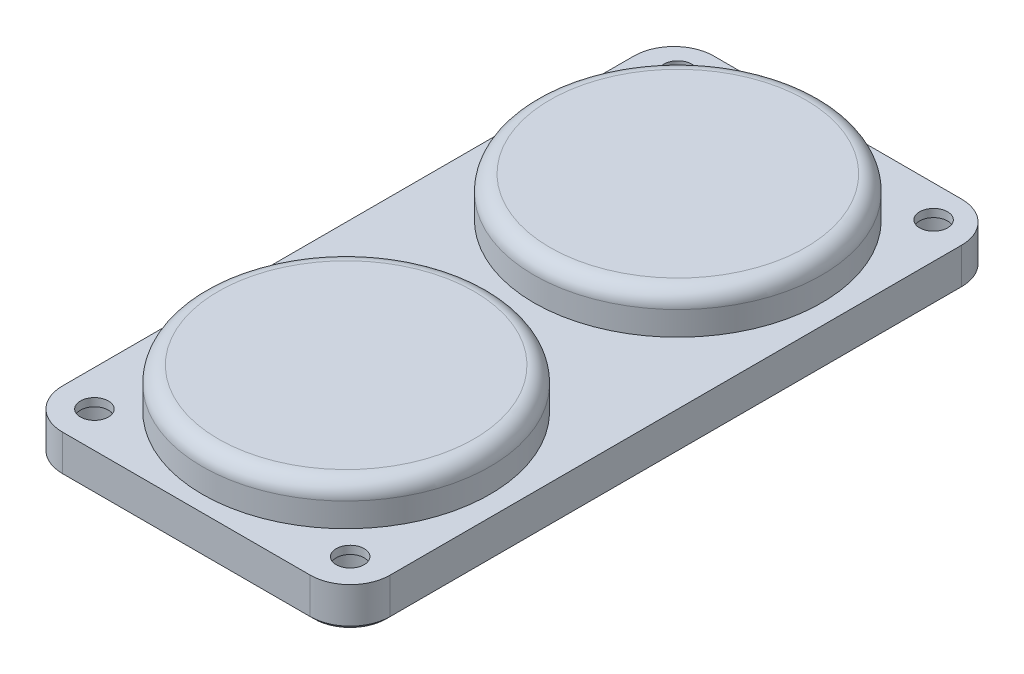
SolidWorks part; units mm, degrees
ref_plane "Front Plane" through (0, 0, 0) normal (0, 0, 1) x (1, 0, 0)
ref_plane "Top Plane" through (0, 0, 0) normal (0, 1, 0) x (1, 0, 0)
ref_plane "Right Plane" through (0, 0, 0) normal (1, 0, 0) x (0, 0, -1)
sketch "Sketch1" plane through (0, 0, 0) normal (0, 1, 0) x (1, 0, 0)
  line L0 (-20.5, 56.5) -> (-20.5, -15)
  line L1 (20.5, -20) -> (-20.5, -20) construction
  line L2 (20.5, -20) -> (20.5, 61.5) construction
  line L3 (20.5, 61.5) -> (-20.5, 61.5) construction
  line L4 (-20.5, -20) -> (-20.5, 61.5) construction
  line L5 (16, -20) -> (0.0008, -20) construction
  line L6 (-20.5, -56.5) -> (-20.5, 56.5) construction
  line L7 (-15.5, 61.5) -> (15.5, 61.5)
  line L8 (20.5, 56.5) -> (20.5, -15)
  line L9 (15.5, -20) -> (-15.5, -20)
  arc A0 (-20.5, 56.5) -> (-15.5, 61.5) centre (-15.5, 56.5) cw
  arc A1 (15.5, 61.5) -> (20.5, 56.5) centre (15.5, 56.5) cw
  arc A2 (20.5, -15) -> (15.5, -20) centre (15.5, -15) cw
  arc A3 (-20.5, -15) -> (-15.5, -20) centre (-15.5, -15) ccw
  arc A4 (20.5, 56.5) -> (15.5, 61.5) centre (15.5, 56.5) ccw construction
  point P0 (0, 0)
extrude "Boss-Extrude1" add sketch "Sketch1" against normal blind 5
sketch "Sketch2" plane through (0, -5, 0) normal (0, -1, 0) x (1, 0, 0)
  circle A0 centre (-16, -57.5) radius 1.75
  circle A2 centre (-16, 15.5) radius 1.75
  circle A4 centre (-16, -57.5) radius 1.75 construction
  circle A5 centre (-16, 15.5) radius 1.75 construction
extrude "Cut-Extrude1" cut sketch "Sketch2" against normal through all both and the other way through all
mirror "Mirror1" about plane through (0, 0, 0) normal (1, 0, 0) of "Cut-Extrude1"
sketch "Sketch4" plane through (0, -5, 0) normal (0, -1, 0) x (1, 0, 0)
  line L0 (0, 20) -> (0, -61.5) construction
  line L1 (-15.5, 20) -> (15.5, 20) construction
  line L2 (15.5, -61.5) -> (-15.5, -61.5) construction
  point P6 (0, -20.75)
ref_plane "Plane1" through (0, 0, -20.75) normal (0, 0, -1) x (-1, 0, 0)
sketch "Sketch5" plane through (0, 0, 0) normal (0, 1, 0) x (1, 0, 0)
  circle A0 centre (0, 41.5) radius 19 construction
  circle A1 centre (0, 41.5) radius 19 construction
  circle A2 centre (0, 41.5) radius 18
  dimension "D1" = 1
extrude "Boss-Extrude2" add sketch "Sketch5" along normal blind 5
fillet "Fillet1" radius 2 1 edges at (0, 5, -23.5)
mirror "Mirror3" about plane through (0, 0, -20.75) normal (0, 0, -1) of "Fillet1", "Boss-Extrude2"
sketch "Sketch6" plane through (0, -5, 0) normal (0, -1, 0) x (1, 0, 0)
  circle A0 centre (-16, -57.5) radius 3.25
  circle A1 centre (16, 15.5) radius 3.25
  circle A2 centre (-16, -57.5) radius 1.75 construction
  circle A3 centre (-16, 15.5) radius 3.25
  circle A4 centre (16, -57.5) radius 3.25
  circle A5 centre (16, -57.5) radius 1.75 construction
  dimension "D1" = 6.5
extrude "Cut-Extrude3" cut sketch "Sketch6" against normal blind 4
chamfer "Chamfer1" distance 0.5 angle 45 8 edges at (20.5, -5, -20.75) (19.0355, -5, -60.0355) (19.0355, -5, 18.5355) (0, -5, -61.5) (0, -5, 20) (-19.0355, -5, -60.0355) (-19.0355, -5, 18.5355) (-20.5, -5, -20.75)
